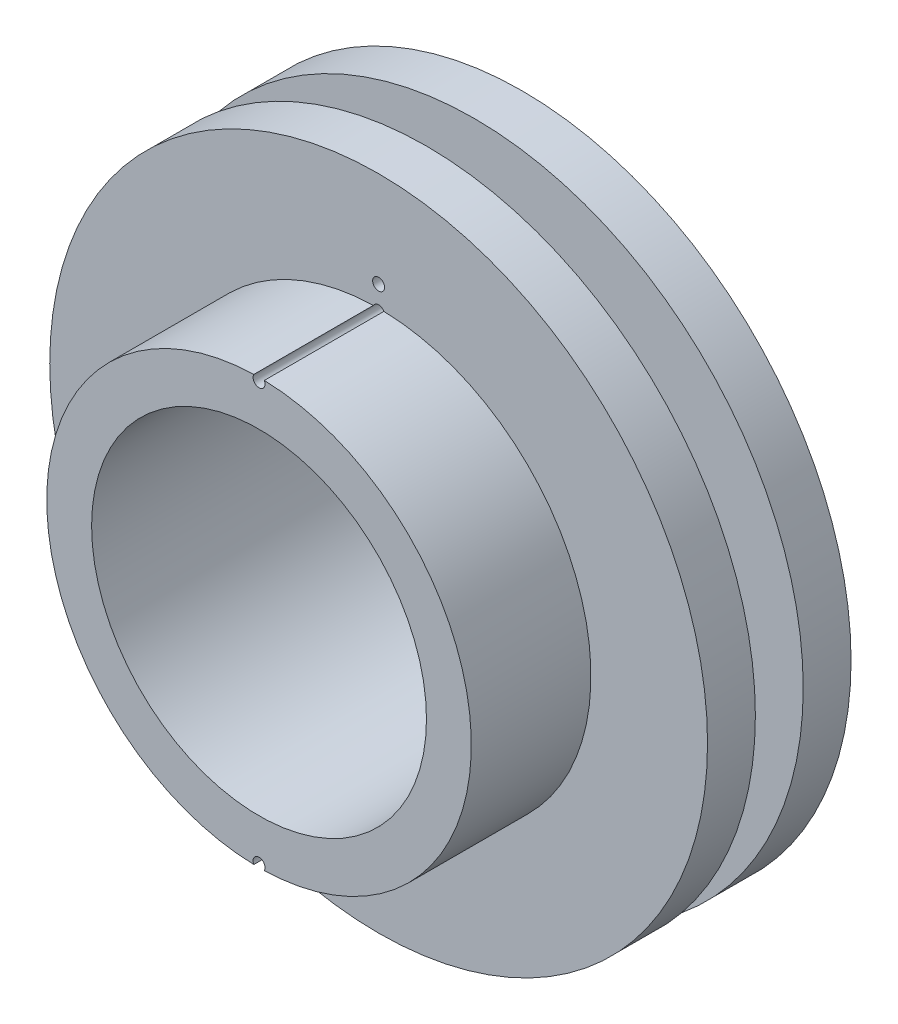
SolidWorks part; units mm, degrees
material "ABS"
ref_plane "Front Plane" through (0, 0, 0) normal (0, 0, 1) x (1, 0, 0)
ref_plane "Top Plane" through (0, 0, 0) normal (0, 1, 0) x (1, 0, 0)
ref_plane "Right Plane" through (0, 0, 0) normal (1, 0, 0) x (0, 0, -1)
sketch "Sketch1" plane through (0, 0, 0) normal (0, 0, 1) x (1, 0, 0)
  circle A0 centre (0, 0) radius 13.75
  dimension "D1" = 27.5
extrude "Boss-Extrude1" add sketch "Sketch1" along normal blind 2
sketch "Sketch2" plane through (0, 0, 0) normal (0, 0, 1) x (1, 0, 0)
  circle A0 centre (0, 0) radius 8.5
  dimension "D1" = 17
extrude "Boss-Extrude2" add sketch "Sketch2" along normal blind 6
sketch "Sketch3" plane through (0, 0, 0) normal (0, 0, 1) x (1, 0, 0)
  circle A0 centre (0, 0) radius 13.75
  dimension "D1" = 27.5
extrude "Boss-Extrude3" add sketch "Sketch3" along normal blind 2 from offset 4
sketch "Sketch5" plane through (0, 0, 0) normal (0, 0, 1) x (1, 0, 0)
  circle A0 centre (0, 0) radius 7
extrude "Cut-Extrude2" cut sketch "Sketch5" along normal through all
sketch "Sketch6" plane through (0, 0, 0) normal (0, 0, 1) x (1, 0, 0)
  circle A0 centre (0, 0) radius 7
  circle A1 centre (0, 0) radius 8.875
  dimension "D1" = 17.75
extrude "Boss-Extrude4" add sketch "Sketch6" along normal blind 5 from surface at 6 starting at face at (13.75, 0, 6)
sketch "Sketch9" plane through (0, 0, 0) normal (0, 0, 1) x (1, 0, 0)
  circle A0 centre (0, 9.75) radius 0.25
  circle A1 centre (0, -9.75) radius 0.25
  circle A2 centre (0, 8.75) radius 0.25
  circle A3 centre (0, -8.75) radius 0.25
extrude "Cut-Extrude3" cut sketch "Sketch9" along normal through all from surface at 4 starting at face at (13.75, 0, 4)
